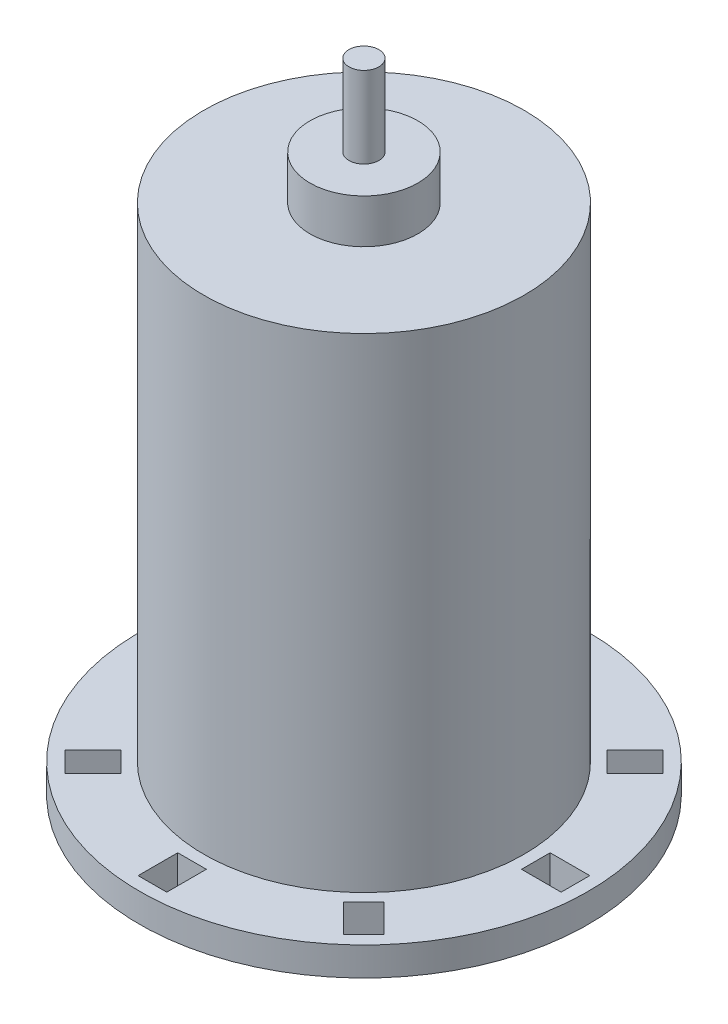
SolidWorks part; units mm, degrees
ref_plane "Přední rovina" through (0, 0, 0) normal (0, 0, 1) x (1, 0, 0)
ref_plane "Horní rovina" through (0, 0, 0) normal (0, 1, 0) x (1, 0, 0)
ref_plane "Pravá rovina" through (0, 0, 0) normal (1, 0, 0) x (0, 0, -1)
sketch "Skica1" plane through (0, 0, 0) normal (0, 1, 0) x (1, 0, 0)
  circle A0 centre (0, 0) radius 16.78
  dimension "D1" = 33.56
extrude "Přidat vysunutím1" add sketch "Skica1" along normal blind 50.7
sketch "Skica2" plane through (0, 50.7, 0) normal (0, 1, 0) x (1, 0, 0)
  circle A0 centre (0, 0) radius 5.65
  dimension "D1" = 11.3
extrude "Přidat vysunutím2" add sketch "Skica2" along normal blind 4.61
sketch "Skica3" plane through (0, 55.31, 0) normal (0, 1, 0) x (1, 0, 0)
  circle A0 centre (0, 0) radius 1.565
  dimension "D1" = 3.13
extrude "Přidat vysunutím3" add sketch "Skica3" along normal blind 8.5
sketch "Sketch6" plane through (0, 0, 0) normal (0, -1, 0) x (1, 0, 0)
  circle A0 centre (0, 0) radius 23.5
  dimension "D1" = 47
extrude "Boss-Extrude1" add sketch "Sketch6" along normal blind 3
sketch "Sketch8" plane through (0, 0, 0) normal (0, 1, 0) x (1, 0, 0)
  line L1 (18, -1.5) -> (22.15, -1.5)
  line L2 (18, -1.5) -> (18, 1.5)
  line L3 (18, 1.5) -> (22.15, 1.5)
  line L4 (22.15, -1.5) -> (22.15, 1.5)
  line L5 (18, -1.5) -> (22.15, 1.5) construction
  line L6 (18, 1.5) -> (22.15, -1.5) construction
  line L10 (0, 0) -> (26.7948, 0) construction
  line L16 (11.6673, -13.7886) -> (14.6018, -16.7231)
  line L22 (11.6673, -13.7886) -> (13.7886, -11.6673)
  line L26 (13.7886, -11.6673) -> (16.7231, -14.6018)
  line L28 (14.6018, -16.7231) -> (16.7231, -14.6018)
  line L32 (11.6673, -13.7886) -> (16.7231, -14.6018) construction
  line L34 (13.7886, -11.6673) -> (14.6018, -16.7231) construction
  line L65 (-1.5, -18) -> (-1.5, -22.15)
  line L66 (-1.5, -18) -> (1.5, -18)
  line L67 (1.5, -18) -> (1.5, -22.15)
  line L68 (-1.5, -22.15) -> (1.5, -22.15)
  line L69 (-1.5, -18) -> (1.5, -22.15) construction
  line L70 (1.5, -18) -> (-1.5, -22.15) construction
  line L71 (-13.7886, -11.6673) -> (-16.7231, -14.6018)
  line L72 (-13.7886, -11.6673) -> (-11.6673, -13.7886)
  line L73 (-11.6673, -13.7886) -> (-14.6018, -16.7231)
  line L74 (-16.7231, -14.6018) -> (-14.6018, -16.7231)
  line L75 (-13.7886, -11.6673) -> (-14.6018, -16.7231) construction
  line L76 (-11.6673, -13.7886) -> (-16.7231, -14.6018) construction
  line L77 (-18, 1.5) -> (-22.15, 1.5)
  line L78 (-18, 1.5) -> (-18, -1.5)
  line L79 (-18, -1.5) -> (-22.15, -1.5)
  line L80 (-22.15, 1.5) -> (-22.15, -1.5)
  line L81 (-18, 1.5) -> (-22.15, -1.5) construction
  line L82 (-18, -1.5) -> (-22.15, 1.5) construction
  line L83 (-11.6673, 13.7886) -> (-14.6018, 16.7231)
  line L84 (-11.6673, 13.7886) -> (-13.7886, 11.6673)
  line L85 (-13.7886, 11.6673) -> (-16.7231, 14.6018)
  line L86 (-14.6018, 16.7231) -> (-16.7231, 14.6018)
  line L87 (-11.6673, 13.7886) -> (-16.7231, 14.6018) construction
  line L88 (-13.7886, 11.6673) -> (-14.6018, 16.7231) construction
  line L89 (1.5, 18) -> (1.5, 22.15)
  line L90 (1.5, 18) -> (-1.5, 18)
  line L91 (-1.5, 18) -> (-1.5, 22.15)
  line L92 (1.5, 22.15) -> (-1.5, 22.15)
  line L93 (1.5, 18) -> (-1.5, 22.15) construction
  line L94 (-1.5, 18) -> (1.5, 22.15) construction
  line L95 (13.7886, 11.6673) -> (16.7231, 14.6018)
  line L96 (13.7886, 11.6673) -> (11.6673, 13.7886)
  line L97 (11.6673, 13.7886) -> (14.6018, 16.7231)
  line L98 (16.7231, 14.6018) -> (14.6018, 16.7231)
  line L99 (13.7886, 11.6673) -> (14.6018, 16.7231) construction
  line L100 (11.6673, 13.7886) -> (16.7231, 14.6018) construction
  line L105 (14.1952, -14.1952) -> (-30.4816, 30.4816) construction
  line L106 (14.1952, -14.1952) -> (21.657, -21.657) construction
  line L107 (-16.7231, -16.7231) -> (19.1989, 19.1989) construction
  line L108 (-16.7231, -16.7231) -> (-19.2003, -19.2003) construction
  line L109 (6.1518, -8.2731) -> (9.0863, -11.2076)
  line L110 (6.1518, -8.2731) -> (8.2731, -6.1518)
  line L111 (9.0863, -11.2076) -> (11.2076, -9.0863)
  line L112 (8.2731, -6.1518) -> (11.2076, -9.0863)
  line L113 (6.1518, -8.2731) -> (11.2076, -9.0863) construction
  line L114 (9.0863, -11.2076) -> (8.2731, -6.1518) construction
  line L115 (-8.2731, -6.1518) -> (-11.2076, -9.0863)
  line L116 (-8.2731, -6.1518) -> (-6.1518, -8.2731)
  line L117 (-6.1518, -8.2731) -> (-9.0863, -11.2076)
  line L118 (-11.2076, -9.0863) -> (-9.0863, -11.2076)
  line L119 (-6.1518, 8.2731) -> (-9.0863, 11.2076)
  line L120 (-6.1518, 8.2731) -> (-8.2731, 6.1518)
  line L121 (-8.2731, 6.1518) -> (-11.2076, 9.0863)
  line L122 (-9.0863, 11.2076) -> (-11.2076, 9.0863)
  line L123 (8.2731, 6.1518) -> (11.2076, 9.0863)
  line L124 (8.2731, 6.1518) -> (6.1518, 8.2731)
  line L125 (6.1518, 8.2731) -> (9.0863, 11.2076)
  line L126 (11.2076, 9.0863) -> (9.0863, 11.2076)
  circle A0 centre (0, 0) radius 16.78 construction
  point P0 (20.075, 0)
  point P12 (14.1952, -14.1952)
  point P17 (0, -20.075)
  point P22 (-14.1952, -14.1952)
  point P25 (0, 0)
  point P28 (0, 0)
  point P29 (-20.075, 0)
  point P34 (-14.1952, 14.1952)
  point P41 (0, 20.075)
  point P46 (14.1952, 14.1952)
  point P51 (0, 0)
  point P56 (8.6797, -8.6797)
  point P59 (0, 0)
  point P76 (0, 0)
  dimension "D1" = 4.15
  dimension "D2" = 3
  dimension "D3" = 18
  dimension "D5" = 8
  dimension "D4" = 1.5
  dimension "D6" = 4.15
  dimension "D7" = 3
  dimension "D8" = 1.5
  dimension "D9" = 3.65
sketch "Skica4" plane through (0, -3, 0) normal (0, -1, 0) x (1, 0, 0)
extrude "Odebrat vysunutím2" cut sketch "Sketch8" against normal blind 3
